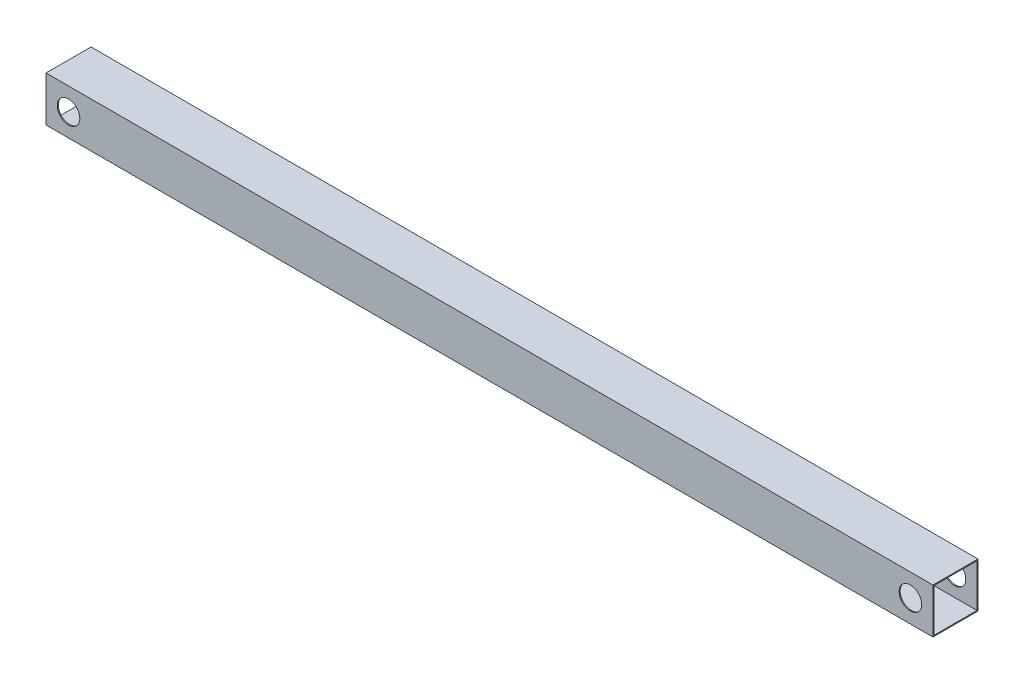
SolidWorks part; units mm, degrees
ref_plane "Alzado" through (0, 0, 0) normal (0, 0, 1) x (1, 0, 0)
ref_plane "Planta" through (0, 0, 0) normal (0, 1, 0) x (1, 0, 0)
ref_plane "Vista lateral" through (0, 0, 0) normal (1, 0, 0) x (0, 0, -1)
sketch "Croquis1" plane through (0, 0, 0) normal (0, 0, 1) x (1, 0, 0)
  line L0 (0, 0) -> (500, 0)
  dimension "D1" = 500
other "Al tube (square) 1 SQ X .022 WALL(3)"
ref_plane "Plano1" through (0, 0, 0) normal (1, 0, 0) x (0, 1, 0)
sketch "Sketch1" plane through (0, 0, 0) normal (1, 0, 0) x (0, 1, 0)
  line L0 (-12.1412, -12.1412) -> (-12.1412, 12.1412)
  line L1 (12.1412, 12.1412) -> (-12.1412, 12.1412)
  line L2 (12.1412, 12.1412) -> (12.1412, -12.1412)
  line L3 (-12.1412, -12.1412) -> (12.1412, -12.1412)
  line L4 (-12.7, -12.7) -> (12.7, -12.7)
  line L5 (-12.7, -12.7) -> (-12.7, 12.7)
  line L6 (12.7, 12.7) -> (-12.7, 12.7)
  line L7 (12.7, 12.7) -> (12.7, -12.7)
  line L8 (0, -12.1412) -> (0, -12.7) construction
  line L9 (0, -12.1412) -> (0, 12.1412) construction
  line L10 (0, 12.1412) -> (0, 12.7) construction
  line L11 (12.7, 0) -> (12.1412, 0) construction
  line L12 (12.1412, 0) -> (-12.1412, 0) construction
  line L13 (-12.1412, 0) -> (-12.7, 0) construction
  point P14 (0, 0)
  dimension "Thickness" = 0.5588
  dimension "V_leg" = 25.4
  dimension "H_leg" = 25.4
sketch "Croquis3" plane through (0, 0, 12.7) normal (0, 0, 1) x (1, 0, 0)
  line L0 (0, 0) -> (500, 0) construction
  line L1 (0, 12.7) -> (0, -12.7) construction
  line L2 (500, 12.7) -> (500, -12.7) construction
  circle A0 centre (12.7, 0) radius 6.35
  circle A1 centre (487.3, 0) radius 6.35
  dimension "D1" = 12.7
  dimension "D2" = 12.7
  dimension "D3" = 12.7
extrude "Cortar-Extruir1" cut sketch "Croquis3" against normal through all
